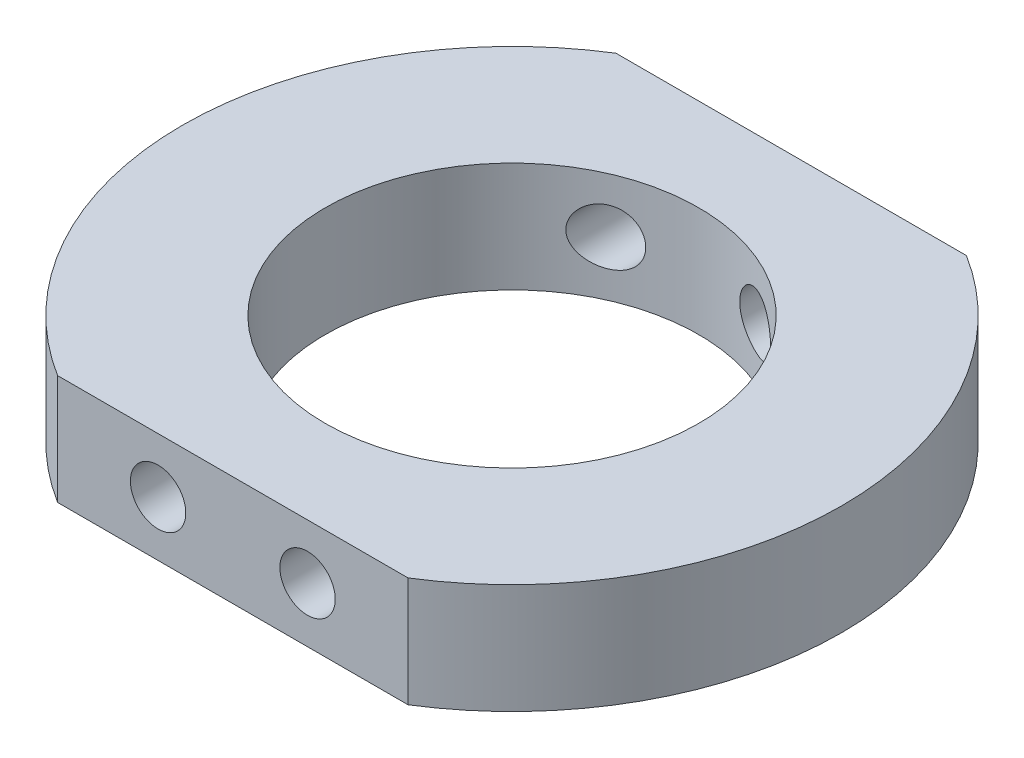
SolidWorks part; units mm, degrees
ref_plane "Front Plane" through (0, 0, 0) normal (0, 0, 1) x (1, 0, 0)
ref_plane "Top Plane" through (0, 0, 0) normal (0, 1, 0) x (1, 0, 0)
ref_plane "Right Plane" through (0, 0, 0) normal (1, 0, 0) x (0, 0, -1)
sketch "Sketch1" plane through (0, 0, 0) normal (0, 1, 0) x (1, 0, 0)
  circle A0 centre (0, 0) radius 38.1
  dimension "D1" = 76.2
extrude "Extrude2" add sketch "Sketch1" against normal blind 12.7
sketch "Sketch5" plane through (0, 0, 0) normal (0, 1, 0) x (1, 0, 0)
  circle A0 centre (0, 0) radius 21.59
  dimension "D1" = 43.18
extrude "Extrude3" cut sketch "Sketch5" against normal through all
sketch "Sketch6" plane through (0, 0, 0) normal (0, 1, 0) x (1, 0, 0)
  line L0 (-20.2571, 32.2686) -> (20.2571, 32.2686)
  line L1 (-20.2571, 32.2686) -> (-20.2571, -32.2686) construction
  line L2 (20.2571, 32.2686) -> (20.2571, -32.2686) construction
  circle A0 centre (0, 0) radius 38.1 construction
  dimension "D1" = 40.5142
extrude "Extrude4" cut sketch "Sketch6" against normal through all and the other way through all contours L0
sketch "Sketch7" plane through (0, 0, 0) normal (0, 1, 0) x (1, 0, 0)
  line L0 (-20.2571, -32.2686) -> (20.2571, -32.2686)
  line L1 (-20.2571, -32.2686) -> (-20.2571, 32.2686) construction
  line L2 (20.2571, 32.2686) -> (-20.2571, 32.2686) construction
  line L3 (20.2571, -32.2686) -> (20.2571, 32.2686) construction
  circle A0 centre (0, 0) radius 38.1 construction
  dimension "D1" = 40.5142
extrude "Extrude5" cut sketch "Sketch7" against normal through all and the other way through all flip side to cut
sketch "Sketch8" plane through (0, 0, -32.2686) normal (0, 0, -1) x (-1, 0, 0)
  line L0 (-20.2571, -6.35) -> (20.2571, -6.35) construction
  line L1 (-20.2571, 0) -> (-20.2571, -12.7) construction
  line L2 (20.2571, 0) -> (20.2571, -12.7) construction
  line L3 (-20.2571, 0) -> (20.2571, 0) construction
  line L4 (-20.2571, -12.7) -> (20.2571, -12.7) construction
  line L5 (0, -12.7) -> (0, 0) construction
  point P10 (-8.636, -6.35)
  point P11 (8.636, -6.35)
  dimension "D1" = 8.636
hole_wizard "M6 Clearance Hole1" positions "3DSketch2" profile "Sketch9" hole size "M6" standard "Ansi Metric" end condition through all
sketch3d "3DSketch2"
  point P0 (8.636, -6.35, -32.2686)
  point P3 (-8.636, -6.35, -32.2686)
sketch "Sketch9" plane through (8.636, -6.35, -32.2686) normal (1, 0, 0) x (0, 1, 0)
  line L0 (0, 0) -> (0, 64.5371)
  line L1 (0, 64.5371) -> (3.2, 64.5371)
  line L2 (3.2, 64.5371) -> (3.2, 0)
  line L5 (3.2, 0) -> (0, 0)
  line L11 (0, -6.35) -> (0, 107.95) construction
  dimension "Thru Hole Dia." = 6.4
  dimension "Thru Hole Depth" = 64.5371
